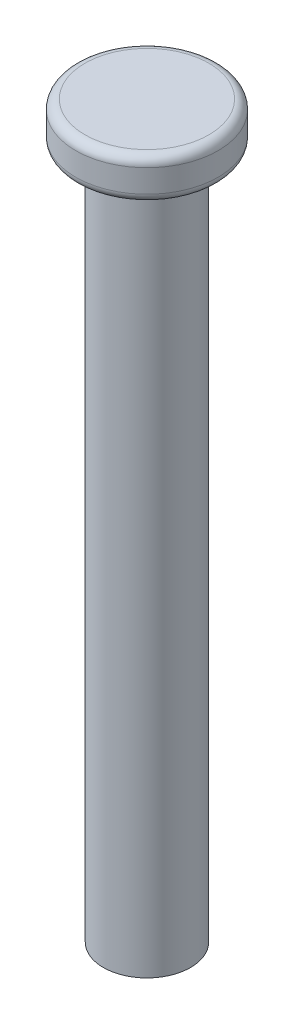
SolidWorks part; units mm, degrees
ref_plane "Front Plane" through (0, 0, 0) normal (0, 0, 1) x (1, 0, 0)
ref_plane "Top Plane" through (0, 0, 0) normal (0, 1, 0) x (1, 0, 0)
ref_plane "Right Plane" through (0, 0, 0) normal (1, 0, 0) x (0, 0, -1)
sketch "Sketch1" plane through (0, 0, 0) normal (0, 1, 0) x (1, 0, 0)
  circle A0 centre (0, 0) radius 1.2065
  dimension "D1" = 2.413
extrude "Boss-Extrude1" add sketch "Sketch1" along normal blind 19.05
sketch "Sketch2" plane through (0, 19.05, 0) normal (0, 1, 0) x (1, 0, 0)
  circle A0 centre (0, 0) radius 1.9685
  dimension "D1" = 3.937
extrude "Boss-Extrude2" add sketch "Sketch2" along normal blind 1.143
fillet "Fillet1" radius 0.254 2 edges at (0, 19.05, 1.9685) (0, 20.193, 1.9685)
